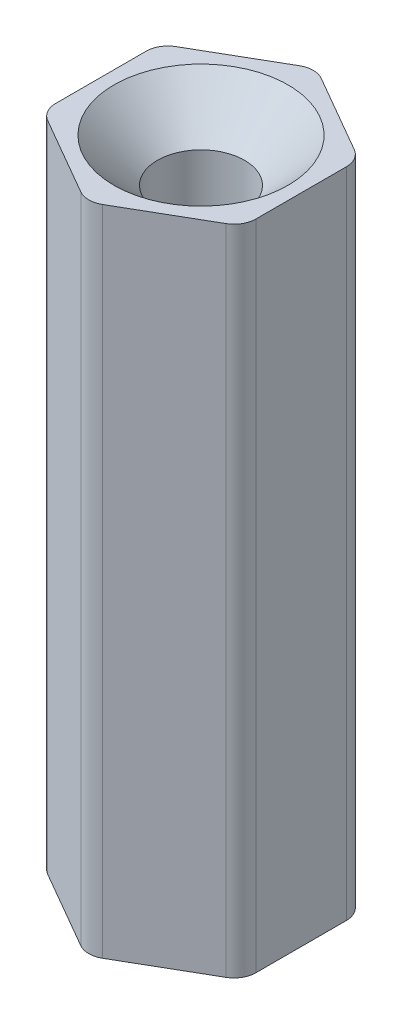
SolidWorks part; units mm, degrees
material "Free-Cutting Brass, UNS C36000"
ref_plane "Front" through (0, 0, 0) normal (0, 0, 1) x (1, 0, 0)
ref_plane "Top" through (0, 0, 0) normal (0, 1, 0) x (1, 0, 0)
ref_plane "Right" through (0, 0, 0) normal (1, 0, 0) x (0, 0, -1)
sketch "Sketch1" plane through (0, 0, 0) normal (0, 1, 0) x (1, 0, 0)
  line L1 (0, 2.6558) -> (-2.3, 1.3279)
  line L2 (-2.3, 1.3279) -> (-2.3, -1.3279)
  line L3 (-2.3, -1.3279) -> (0, -2.6558)
  line L4 (0, -2.6558) -> (2.3, -1.3279)
  line L5 (2.3, -1.3279) -> (2.3, 1.3279)
  line L6 (2.3, 1.3279) -> (0, 2.6558)
  circle A0 centre (0, 0) radius 2.3 construction
  dimension "D1" = 4.6
extrude "Boss-Extrude1" add sketch "Sketch1" along normal blind 15
sketch "Sketch2" plane through (0, 15, 0) normal (0, 1, 0) x (1, 0, 0)
  circle A0 centre (0, 0) radius 1
  dimension "D1" = 2
extrude "Cut-Extrude1" cut sketch "Sketch2" against normal through all
chamfer "Chamfer2" distance 1 angle 45 2 edges at (0, 0, 1) (0, 15, 1)
fillet "Fillet1" radius 0.5 6 edges at (0, 7.5, 2.6558) (-2.3, 7.5, 1.3279) (-2.3, 7.5, -1.3279) (0, 7.5, -2.6558) (2.3, 7.5, -1.3279) (2.3, 7.5, 1.3279)
